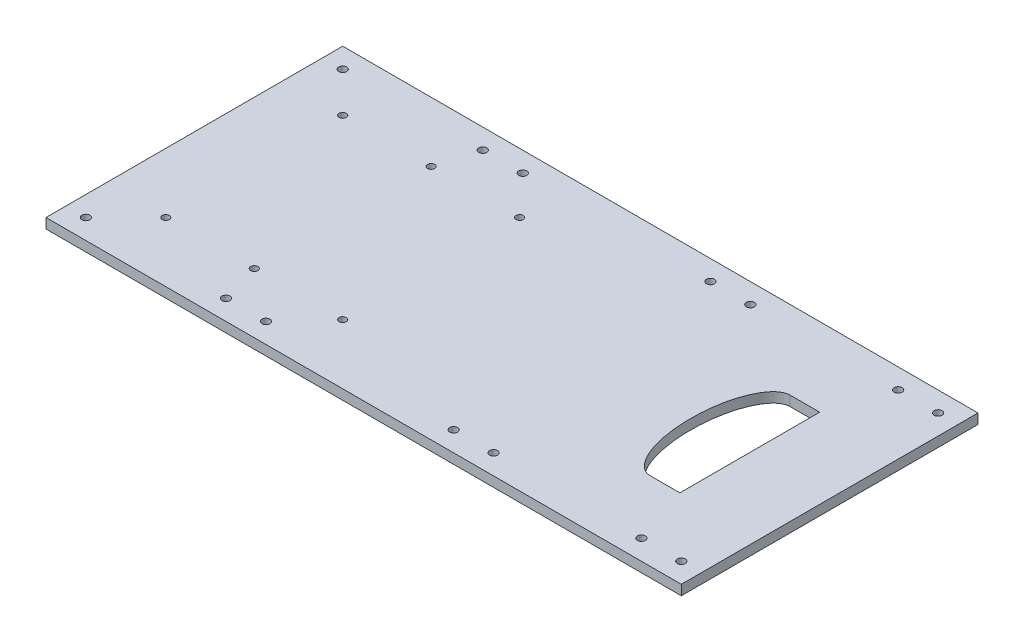
SolidWorks part; units mm, degrees
material "PMMA"
ref_plane "Plan de face" through (0, 0, 0) normal (0, 0, 1) x (1, 0, 0)
ref_plane "Plan de dessus" through (0, 0, 0) normal (0, 1, 0) x (1, 0, 0)
ref_plane "Plan de droite" through (0, 0, 0) normal (1, 0, 0) x (0, 0, -1)
sketch "Esquisse2" plane through (0, 0, 0) normal (0, 1, 0) x (1, 0, 0)
  line L0 (-31.7655, -2.8878) -> (286.3845, -2.8878)
  line L2 (-31.7655, -2.8878) -> (286.3845, -2.8878)
  line L3 (-31.7655, -2.8878) -> (-31.7655, -151.4778)
  line L4 (-31.7655, -151.4778) -> (286.3845, -151.4778)
  line L5 (286.3845, -2.8878) -> (286.3845, -151.4778)
extrude "Boss.-Extru.1" add sketch "Esquisse2" along normal blind 5 contours L5 L0 L3 L4
sketch "Esquisse3" plane through (0, 5, 0) normal (0, 1, 0) x (1, 0, 0)
  line L0 (-31.7655, -151.4778) -> (-31.7655, -141.4778)
  line L1 (-31.7655, -2.8878) -> (-31.7655, -151.4778) construction
  line L2 (-31.7655, -141.4778) -> (-21.7655, -141.4778)
  line L3 (-31.7655, -2.8878) -> (-21.7655, -2.8878)
  line L4 (-31.7655, -2.8878) -> (286.3845, -2.8878) construction
  line L5 (-21.7655, -2.8878) -> (-21.7655, -12.8878)
  line L6 (286.3845, -2.8878) -> (286.3845, -12.8878)
  line L7 (286.3845, -2.8878) -> (286.3845, -151.4778) construction
  line L8 (286.3845, -12.8878) -> (276.3845, -12.8878)
  line L9 (286.3845, -151.4778) -> (276.3845, -151.4778)
  line L10 (-31.7655, -151.4778) -> (286.3845, -151.4778) construction
  line L11 (276.3845, -151.4778) -> (276.3845, -141.4778)
  circle A0 centre (276.3845, -141.4778) radius 2
  circle A1 centre (276.3845, -12.8878) radius 2
  circle A2 centre (-21.7655, -12.8878) radius 2
  circle A3 centre (-21.7655, -141.4778) radius 2
extrude "Enlèv. mat.-Extru.1" cut sketch "Esquisse3" against normal blind 5
sketch "Esquisse6" plane through (0, 0, 0) normal (0, -1, 0) x (-1, 0, 0)
  line L0 (-158.3174, -94.3061) -> (-178.3174, -94.3061)
  line L1 (-178.3174, -94.3061) -> (-178.3174, -60.0595)
  line L2 (-178.3174, -60.0595) -> (-158.3174, -60.0595)
  line L8 (-161.9825, -37.1828) -> (-141.9825, -37.1828)
  line L9 (-161.9825, -117.1828) -> (-141.9825, -117.1828)
  spline S0 degree 2 poles (-141.9825, -117.1828) (-181.9825, -77.1828) (-141.9825, -37.1828) knots 0 0 0 1 1 1
  spline S1 degree 2 poles (-161.9825, -117.1828) (-201.9825, -77.1828) (-161.9825, -37.1828) knots 0 0 0 1 1 1
sketch "Esquisse7" plane through (0, 0, 0) normal (0, -1, 0) x (-1, 0, 0)
  line L0 (31.7655, -151.4778) -> (31.7655, -77.1828)
  line L1 (31.7655, -2.8878) -> (31.7655, -151.4778) construction
  line L2 (11.7655, -72.1828) -> (11.7655, -82.1828)
  line L5 (1.7655, -72.1828) -> (11.7655, -72.1828)
  line L6 (11.7655, -82.1828) -> (1.7655, -82.1828)
  line L7 (1.7655, -72.1828) -> (1.7655, -82.1828)
sketch "Esquisse8" plane through (0, 0, 0) normal (0, -1, 0) x (1, 0, 0)
  line L0 (96.8245, 131.4778) -> (96.8245, 22.8878)
  line L3 (96.8245, 131.4778) -> (96.8245, 121.4778)
  line L4 (-11.7655, 22.8878) -> (96.8245, 22.8878)
  line L5 (96.8245, 121.4778) -> (86.8245, 121.4778)
  line L6 (96.8245, 22.8878) -> (86.8245, 22.8878)
  line L7 (-11.7655, 131.4778) -> (-11.7655, 22.8878)
  line L8 (86.8245, 22.8878) -> (86.8245, 32.8878)
  line L9 (-11.7655, 131.4778) -> (96.8245, 131.4778)
  line L10 (-11.7655, 22.8878) -> (-1.7655, 22.8878)
  line L11 (-1.7655, 22.8878) -> (-1.7655, 32.8878)
  line L12 (-1.7655, 131.4778) -> (-1.7655, 121.4778)
  line L13 (42.5295, 22.8878) -> (42.5295, 32.8878)
  line L14 (42.5295, 32.8878) -> (42.5295, 121.4778)
  circle A0 centre (-1.7655, 121.4778) radius 1.8
  circle A1 centre (86.8245, 121.4778) radius 1.8
  circle A2 centre (86.8245, 32.8878) radius 1.8
  circle A3 centre (-1.7655, 32.8878) radius 1.8
  circle A4 centre (42.5295, 32.8878) radius 1.8
  circle A5 centre (42.5295, 121.4778) radius 1.8
extrude "Enlèv. mat.-Extru.5" cut sketch "Esquisse8" against normal blind 5
sketch "Esquisse9" plane through (0, 0, 0) normal (0, -1, 0) x (1, 0, 0)
  line L0 (274.3845, 141.4778) -> (184.3845, 141.4778)
  line L1 (274.3845, 12.8878) -> (184.3845, 12.8878)
  line L2 (184.3845, 12.8878) -> (182.3845, 12.8878)
  line L3 (182.3845, 141.4778) -> (162.3845, 141.4778)
  line L4 (182.3845, 12.8878) -> (162.3845, 12.8878)
  line L5 (162.3845, 141.4778) -> (160.3845, 141.4778)
  line L6 (162.3845, 12.8878) -> (160.3845, 12.8878)
  line L7 (162.3845, 14.8878) -> (162.3845, 139.4778)
  line L8 (184.3845, 141.4778) -> (182.3845, 141.4778)
  line L9 (160.3845, 141.4778) -> (70.3845, 141.4778)
  line L10 (70.3845, 141.4778) -> (70.3845, 12.8878)
  line L11 (70.3845, 12.8878) -> (68.3845, 12.8878)
  line L12 (160.3845, 12.8878) -> (70.3845, 12.8878)
  line L13 (70.3845, 141.4778) -> (68.3845, 141.4778)
  line L14 (68.3845, 141.4778) -> (48.3845, 141.4778)
  line L15 (68.3845, 12.8878) -> (48.3845, 12.8878)
  line L16 (48.3845, 141.4778) -> (46.3845, 141.4778)
  line L17 (48.3845, 12.8878) -> (46.3845, 12.8878)
  circle A0 centre (276.3845, 141.4778) radius 2 construction
  circle A1 centre (276.3845, 12.8878) radius 2 construction
  circle A3 centre (182.3845, 12.8878) radius 2
  circle A5 centre (162.3845, 12.8878) radius 2
  circle A6 centre (182.3845, 141.4778) radius 2
  circle A9 centre (162.3845, 141.4778) radius 2
  circle A10 centre (68.3845, 141.4778) radius 2
  circle A11 centre (68.3845, 12.8878) radius 2
  circle A12 centre (48.3845, 12.8878) radius 2
  circle A13 centre (48.3845, 141.4778) radius 2
  dimension "D3" = 20
  dimension "D1" = 90
  dimension "D2" = 90
  dimension "D4" = 20
extrude "Enlèv. mat.-Extru.6" cut sketch "Esquisse9" against normal blind 10 contours A10 | A13 | A9 | A6 | A3 | A5 | A12 | A11
sketch "Esquisse10" plane through (0, 0, 0) normal (0, -1, 0) x (1, 0, 0)
  line L0 (286.3845, 151.4778) -> (266.3845, 151.4778)
  line L1 (-31.7655, 151.4778) -> (286.3845, 151.4778) construction
  line L2 (266.3845, 151.4778) -> (266.3845, 2.8878)
  line L3 (-31.7655, 2.8878) -> (286.3845, 2.8878) construction
  line L4 (266.3845, 2.8878) -> (286.3845, 2.8878)
  line L5 (276.3845, 141.4778) -> (266.3845, 141.4778)
  line L6 (276.3845, 12.8878) -> (266.3845, 12.8878)
  line L7 (266.3845, 141.4778) -> (256.3845, 141.4778)
  line L8 (266.3845, 12.8878) -> (256.3845, 12.8878)
  circle A0 centre (256.3845, 12.8878) radius 2
  circle A1 centre (256.3845, 141.4778) radius 2
extrude "Enlèv. mat.-Extru.8" cut sketch "Esquisse10" against normal blind 10 contours A1 | A0
sketch "Esquisse11" plane through (0, 0, 0) normal (0, -1, 0) x (1, 0, 0)
  line L0 (286.3845, 77.1828) -> (246.3845, 77.1828)
  line L1 (286.3845, 2.8878) -> (286.3845, 151.4778) construction
  line L2 (246.3845, 42.1828) -> (246.3845, 112.1828)
  line L3 (246.3845, 112.1828) -> (216.3845, 112.1828)
  line L4 (246.3845, 42.1828) -> (216.3845, 42.1828)
  line L5 (216.3845, 112.1828) -> (216.3845, 42.1828)
  ellipse E0 centre (231.5913, 77.1828) end of major axis (231.5913, 112.1828) minor radius 14.7932
  point P6 (246.3845, 77.1828)
  point P9 (246.3845, 112.1828)
extrude "Enlèv. mat.-Extru.10" cut sketch "Esquisse11" against normal blind 10 contours E0 L2 L3 | E0 L4 L2
